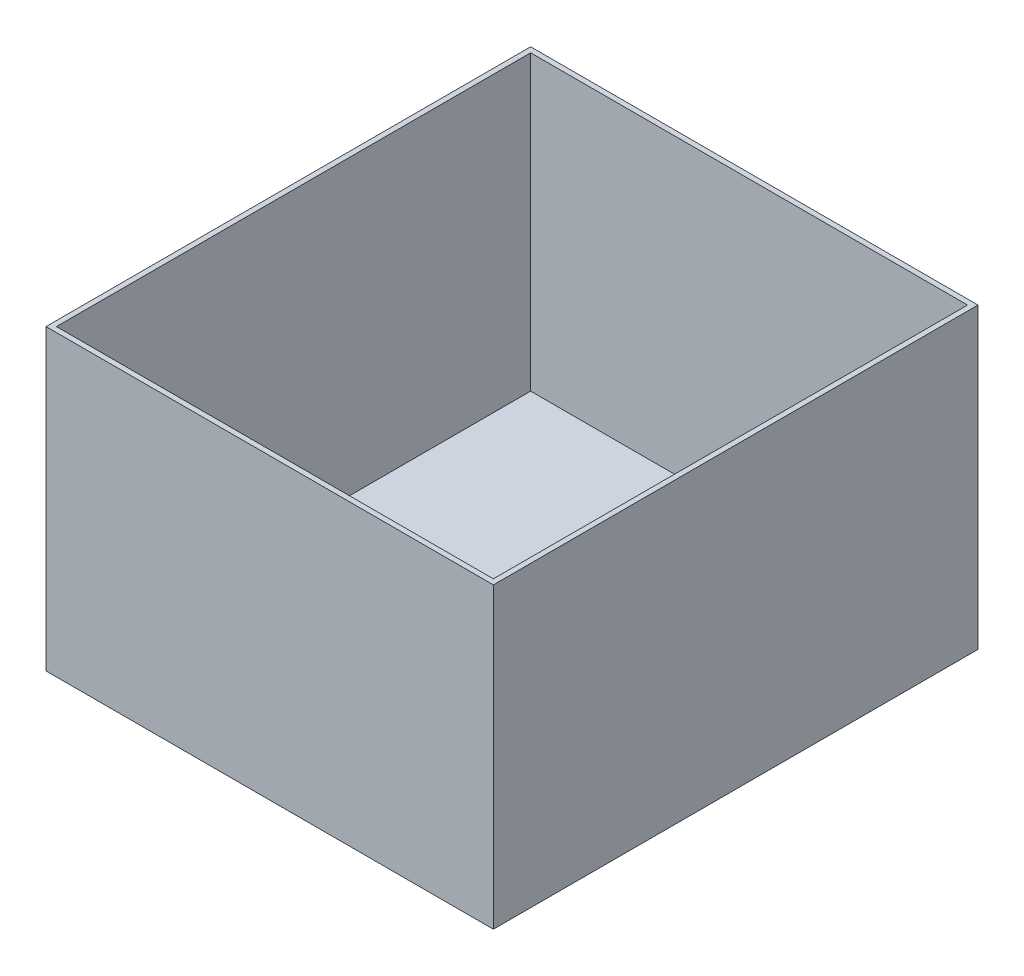
SolidWorks part; units mm, degrees
ref_plane "Front Plane" through (0, 0, 0) normal (0, 0, 1) x (1, 0, 0)
ref_plane "Top Plane" through (0, 0, 0) normal (0, 1, 0) x (1, 0, 0)
ref_plane "Right Plane" through (0, 0, 0) normal (1, 0, 0) x (0, 0, -1)
sketch "Sketch1" plane through (0, 0, 0) normal (0, 1, 0) x (1, 0, 0)
  line L1 (0, 0) -> (152.4, 0)
  line L2 (0, 0) -> (0, 165.1)
  line L3 (0, 165.1) -> (152.4, 165.1)
  line L4 (152.4, 0) -> (152.4, 165.1)
extrude "Boss-Extrude1" add sketch "Sketch1" along normal blind 101.6
sketch "Sketch2" plane through (0, 101.6, 0) normal (0, 1, 0) x (1, 0, 0)
  line L0 (1.778, 163.322) -> (1.778, 1.778)
  line L1 (1.778, 1.778) -> (150.622, 1.778)
  line L2 (150.622, 1.778) -> (150.622, 163.322)
  line L3 (150.622, 163.322) -> (1.778, 163.322)
  dimension "D1" = 148.844
  dimension "D2" = 161.544
extrude "Cut-Extrude1" cut sketch "Sketch2" against normal blind 99.822 contours L1 L2 L3 L0
